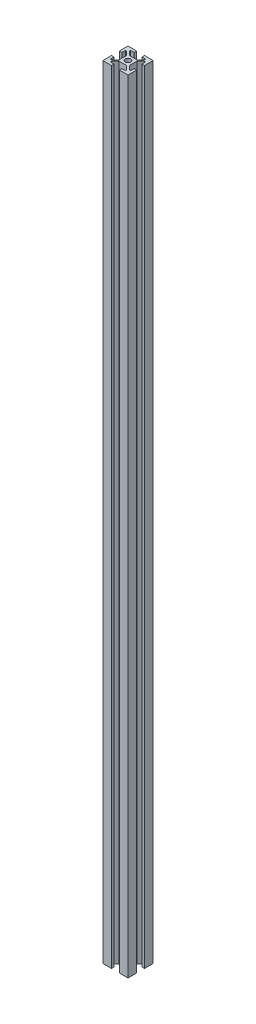
SolidWorks part; units mm, degrees
ref_plane "Front" through (0, 0, 0) normal (0, 0, 1) x (1, 0, 0)
ref_plane "Top" through (0, 0, 0) normal (0, 1, 0) x (1, 0, 0)
ref_plane "Right" through (0, 0, 0) normal (1, 0, 0) x (0, 0, -1)
sketch "스케치1" plane through (0, 0, 0) normal (0, 1, 0) x (1, 0, 0)
  line L0 (3.1, 8) -> (6, 8)
  line L1 (-10.001, 9.999) -> (-3.1, 9.999)
  line L2 (-10.001, 9.999) -> (-10.001, 3.1)
  line L3 (-10.001, -9.999) -> (-3.1, -9.999)
  line L4 (10.001, 9.999) -> (10.001, 3.1)
  line L5 (-10.001, 9.999) -> (-1.5204, 1.5201) construction
  line L6 (-10.001, -9.999) -> (-1.5204, -1.5201) construction
  line L11 (-7, -7) -> (-1.5203, -1.5203) construction
  line L12 (-7, 7) -> (-1.5203, 1.5203) construction
  line L15 (-3.1, 9.999) -> (-3.1, 8)
  line L17 (3.1, 9.999) -> (3.1, 8)
  line L18 (8, -3.1) -> (8, -6)
  line L27 (-3.1, 8) -> (-6, 8)
  line L28 (6, 8) -> (6, 7)
  line L30 (0, 4) -> (3, 4)
  line L31 (3, 4) -> (6, 7)
  line L32 (-6, 8) -> (-6, 7)
  line L33 (-6, 7) -> (-3, 4)
  line L34 (0, 4) -> (-3, 4)
  line L35 (3.1, 9.999) -> (10.001, 9.999)
  line L36 (10.001, 3.1) -> (8, 3.1)
  line L37 (10.001, -3.1) -> (8, -3.1)
  line L38 (8, 3.1) -> (8, 6)
  line L39 (8, -6) -> (7, -6)
  line L40 (4, 0) -> (4, -3)
  line L41 (4, -3) -> (7, -6)
  line L42 (8, 6) -> (7, 6)
  line L43 (7, 6) -> (4, 3)
  line L44 (4, 0) -> (4, 3)
  line L45 (-3.1, -8) -> (-6, -8)
  line L47 (3.1, -9.999) -> (3.1, -8)
  line L48 (-3.1, -9.999) -> (-3.1, -8)
  line L49 (3.1, -8) -> (6, -8)
  line L50 (-6, -8) -> (-6, -7)
  line L51 (0, -4) -> (-3, -4)
  line L52 (-3, -4) -> (-6, -7)
  line L53 (6, -8) -> (6, -7)
  line L54 (6, -7) -> (3, -4)
  line L55 (0, -4) -> (3, -4)
  line L56 (-8, 3.1) -> (-8, 6)
  line L58 (-10.001, -3.1) -> (-8, -3.1)
  line L59 (-10.001, 3.1) -> (-8, 3.1)
  line L60 (-8, -3.1) -> (-8, -6)
  line L61 (-8, 6) -> (-7, 6)
  line L62 (-4, 0) -> (-4, 3)
  line L63 (-4, 3) -> (-7, 6)
  line L64 (-8, -6) -> (-7, -6)
  line L65 (-7, -6) -> (-4, -3)
  line L66 (-4, 0) -> (-4, -3)
  line L67 (-10.001, -3.1) -> (-10.001, -9.999)
  line L69 (3.1, -9.999) -> (10.001, -9.999)
  line L72 (10.001, -3.1) -> (10.001, -9.999)
  line L73 (1.5203, -1.5203) -> (7, -7) construction
  line L74 (1.5204, -1.5201) -> (10.001, -9.999) construction
  line L75 (1.5203, 1.5203) -> (7, 7) construction
  line L76 (1.5204, 1.5201) -> (10.001, 9.999) construction
  circle A4 centre (0, 0) radius 2.15
  point P0 (0, 0)
  point P6 (0, 0)
  point P21 (0, 0)
  point P22 (0, 10)
  point P31 (0, 0)
  point P40 (10, 0)
  point P46 (0, 0)
  point P53 (0, -10)
  point P59 (0, 0)
  point P66 (-10, 0)
  point P72 (0, 0)
  dimension "D1" = 4
extrude "보스-돌출1" add sketch "스케치1" along normal blind 622.3
sketch "스케치3" plane through (10.001, 0, 0) normal (1, 0, 0) x (0, 0, -1)
  line L0 (0, 0) -> (0, 622.3) construction
  line L1 (-3, 622.3) -> (3, 622.3) construction
  circle A0 centre (0, 311.15) radius 3
extrude "컷-돌출1" cut sketch "스케치3" against normal blind 26
